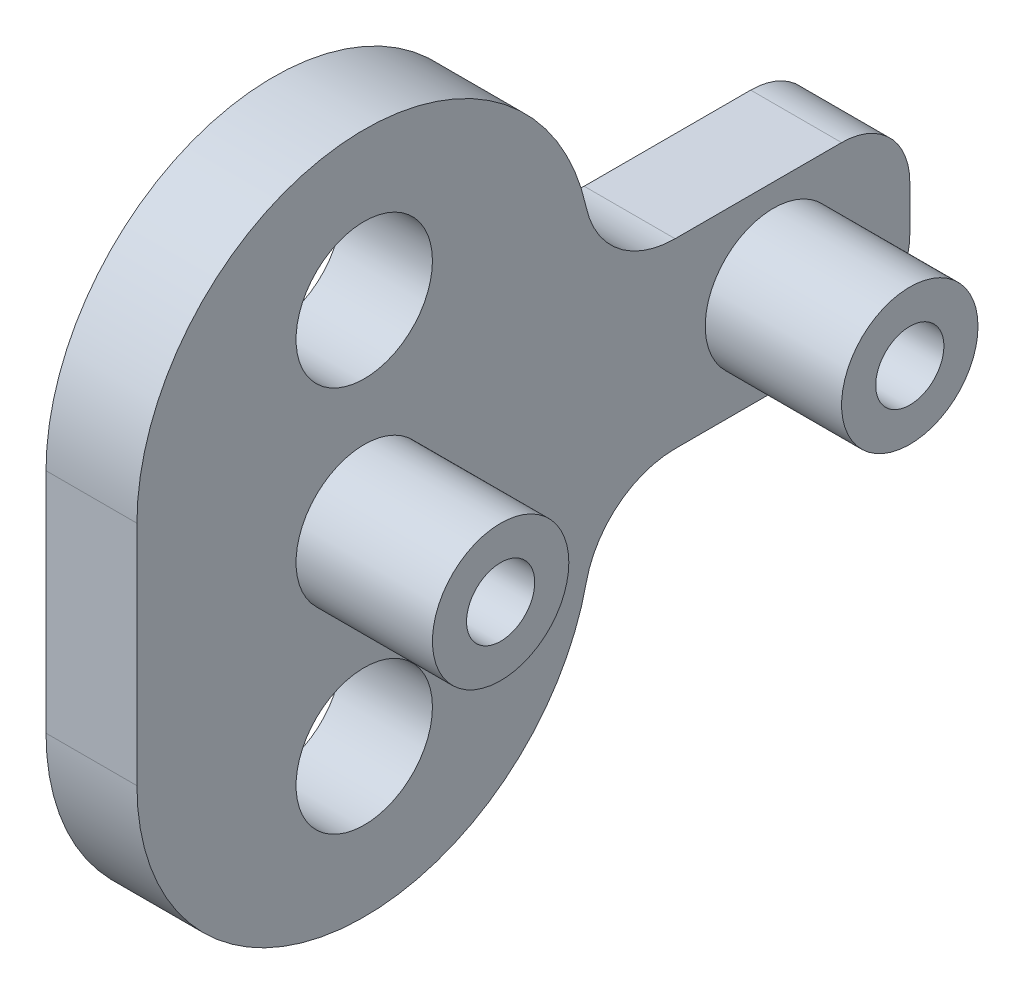
SolidWorks part; units mm, degrees
ref_plane "Front Plane" through (0, 0, 0) normal (0, 0, 1) x (1, 0, 0)
ref_plane "Top Plane" through (0, 0, 0) normal (0, 1, 0) x (1, 0, 0)
ref_plane "Right Plane" through (0, 0, 0) normal (1, 0, 0) x (0, 0, -1)
ref_plane "Plane1" through (24, 0, 0) normal (1, 0, 0) x (0, 0, -1)
sketch "Sketch1" plane through (24, 0, 0) normal (1, 0, 0) x (0, 0, -1)
  line L0 (-96.0431, 96.9723) -> (-110.0933, 96.9723)
  line L1 (-130.0431, 97.9723) -> (-130.0431, 87.9723)
  line L2 (-110.0933, 88.9723) -> (-96.0431, 88.9723)
  line L3 (-96.0431, 88.9723) -> (-96.0431, 96.9723)
  arc A0 (-110.0933, 96.9723) -> (-130.0431, 97.9723) centre (-120.0431, 97.9723) ccw
  arc A1 (-130.0431, 87.9723) -> (-110.0933, 88.9723) centre (-120.0431, 87.9723) ccw
extrude "Boss-Extrude1" add sketch "Sketch1" against normal blind 4
ref_plane "Plane2" through (0, 0, 102.0431) normal (0, 0, 1) x (1, 0, 0)
sketch "Sketch2" plane through (0, 0, 102.0431) normal (0, 0, 1) x (1, 0, 0)
  line L0 (24, 95.9723) -> (24, 92.9723)
  line L1 (24, 92.9723) -> (30, 92.9723)
  line L2 (30, 92.9723) -> (30, 95.9723)
  line L3 (30, 95.9723) -> (24, 95.9723)
  line L4 (24, 92.9723) -> (30, 92.9723) construction
revolve "Revolve1" add sketch "Sketch2" angle 360 about L4
ref_plane "Plane3" through (0, 0, 120.0431) normal (0, 0, 1) x (1, 0, 0)
sketch "Sketch3" plane through (0, 0, 120.0431) normal (0, 0, 1) x (1, 0, 0)
  line L0 (24, 95.9723) -> (24, 92.9723)
  line L1 (24, 92.9723) -> (30, 92.9723)
  line L2 (30, 92.9723) -> (30, 95.9723)
  line L3 (30, 95.9723) -> (24, 95.9723)
  line L4 (24, 92.9723) -> (30, 92.9723) construction
revolve "Revolve2" add sketch "Sketch3" angle 360 about L4
hole_wizard "Ø3.0 (3) Diameter Hole1" positions "Sketch5" profile "Sketch4" hole size "Ø3.0" standard "ANSI Metric"
sketch "Sketch5" plane through (30, 0, 0) normal (1, 0, 0) x (0, 0, -1)
  point P0 (-120.0431, 92.9723)
  point P1 (-102.0431, 92.9723)
sketch "Sketch4" plane through (30, 92.9723, 120.0431) normal (0, 1, 0) x (0, 0, -1)
  line L0 (0, 0) -> (0, 10)
  line L1 (0, 10) -> (1.5, 10)
  line L2 (1.5, 10) -> (1.5, 0)
  line L5 (1.5, 0) -> (0, 0)
  line L11 (0, -6.35) -> (0, 107.95) construction
  dimension "Thru Hole Dia." = 3
  dimension "Thru Hole Depth" = 10
hole_wizard "Ø6.0 (6) Diameter Hole1" positions "Sketch7" profile "Sketch6" hole size "Ø6.0" standard "ANSI Metric"
sketch "Sketch7" plane through (24, 0, 0) normal (1, 0, 0) x (0, 0, -1)
  point P0 (-120.0431, 101.4723)
  point P1 (-120.0431, 84.4723)
sketch "Sketch6" plane through (24, 101.4723, 120.0431) normal (0, 1, 0) x (0, 0, -1)
  line L0 (0, 0) -> (0, 4)
  line L1 (0, 4) -> (3, 4)
  line L2 (3, 4) -> (3, 0)
  line L5 (3, 0) -> (0, 0)
  line L11 (0, -6.35) -> (0, 107.95) construction
  dimension "Thru Hole Dia." = 6
  dimension "Thru Hole Depth" = 4
fillet "Fillet1" radius 3 2 edges at (22, 96.9723, 96.0431) (22, 88.9723, 96.0431)
fillet "Fillet2" radius 4 2 edges at (22, 96.9723, 110.0933) (22, 88.9723, 110.0933)
